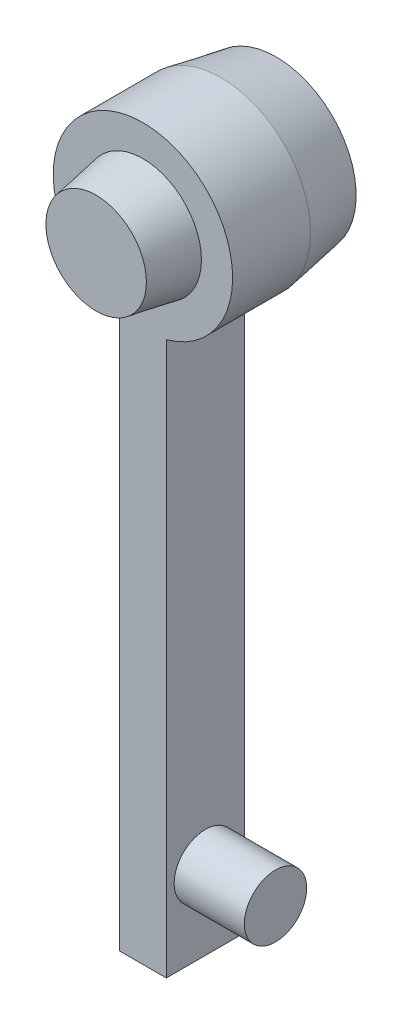
SolidWorks part; units mm, degrees
ref_plane "Ön Düzlem" through (0, 0, 0) normal (0, 0, 1) x (1, 0, 0)
ref_plane "Üst Düzlem" through (0, 0, 0) normal (0, 1, 0) x (1, 0, 0)
ref_plane "Sağ Düzlem" through (0, 0, 0) normal (1, 0, 0) x (0, 0, -1)
sketch "Sketch1" plane through (0, 0, 0) normal (0, 0, 1) x (1, 0, 0)
  line L0 (0, -41) -> (0, 41) construction
  line L2 (3, 29.8982) -> (3, -41)
  line L3 (3, -41) -> (-3, -41)
  line L4 (-3, 29.8982) -> (-3, -41)
  line L5 (-3, 0) -> (3, 0) construction
  arc A0 (3, 29.8982) -> (-3, 29.8982) centre (0, 41) ccw
  point P0 (0, 0)
  dimension "D3" = 23
  dimension "D1" = 82
  dimension "D2" = 6
extrude "Boss-Extrude1" add sketch "Sketch1" along normal mid plane 10 contours A0 L4 L3 L2
sketch "Sketch2" plane through (0, 0, 5) normal (0, 0, 1) x (1, 0, 0)
  circle A0 centre (0, 41) radius 7.5
  dimension "D1" = 15
extrude "Boss-Extrude2" add sketch "Sketch2" along normal blind 6 draft 10
sketch "Sketch3" plane through (3, 0, 0) normal (1, 0, 0) x (0, 0, -1)
  line L0 (-5, 48.5) -> (-5, 33.5) construction
  circle A0 centre (0, -31) radius 4
  point P4 (-5, 41)
  dimension "D1" = 8
  dimension "D2" = 72
extrude "Boss-Extrude3" add sketch "Sketch3" along normal blind 9
sketch "Sketch4" plane through (0, 0, -5) normal (0, 0, -1) x (-1, 0, 0)
  circle A0 centre (0, 41) radius 9
  circle A1 centre (0, 41) radius 11.5
  arc A2 (3, 29.8982) -> (-3, 29.8982) centre (0, 41) ccw construction
  dimension "D1" = 18
extrude "Boss-Extrude4" add sketch "Sketch4" along normal blind 9 draft 10
